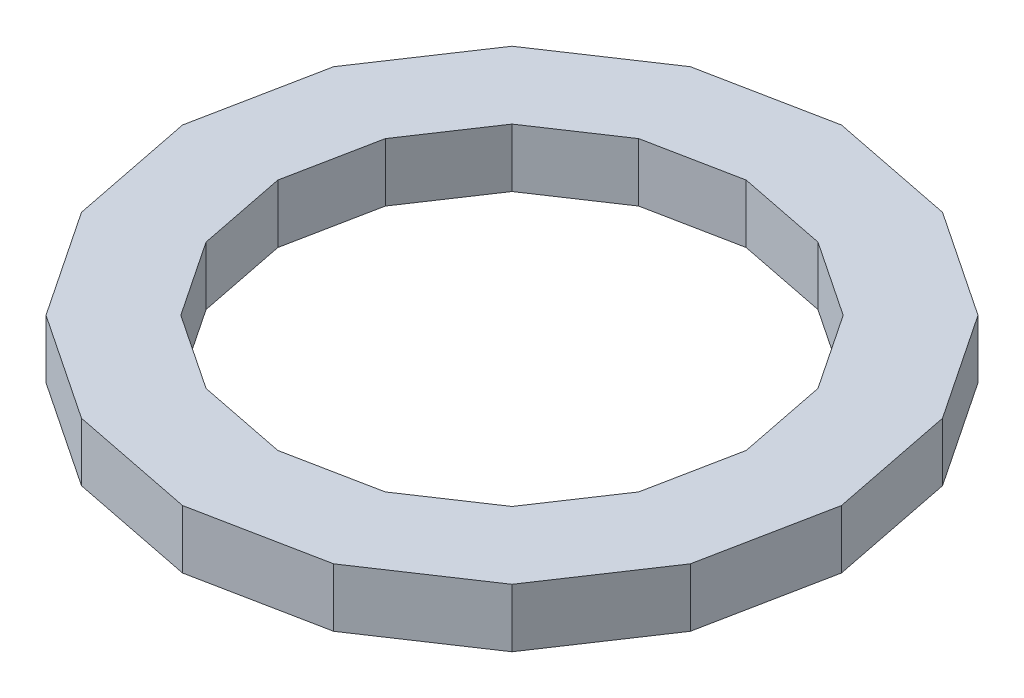
SolidWorks part; units mm, degrees
ref_plane "Front Plane" through (0, 0, 0) normal (0, 0, 1) x (1, 0, 0)
ref_plane "Top Plane" through (0, 0, 0) normal (0, 1, 0) x (1, 0, 0)
ref_plane "Right Plane" through (0, 0, 0) normal (1, 0, 0) x (0, 0, -1)
sketch "Sketch1" plane through (0, 0, 0) normal (0, 1, 0) x (1, 0, 0)
  line L1 (107.4118, 0) -> (99.2356, 41.1047)
  line L2 (99.2356, 41.1047) -> (75.9516, 75.9516)
  line L3 (75.9516, 75.9516) -> (41.1047, 99.2356)
  line L4 (41.1047, 99.2356) -> (0, 107.4118)
  line L5 (0, 107.4118) -> (-41.1047, 99.2356)
  line L6 (-41.1047, 99.2356) -> (-75.9516, 75.9516)
  line L7 (-75.9516, 75.9516) -> (-99.2356, 41.1047)
  line L8 (-99.2356, 41.1047) -> (-107.4118, 0)
  line L9 (-107.4118, 0) -> (-99.2356, -41.1047)
  line L10 (-99.2356, -41.1047) -> (-75.9516, -75.9516)
  line L11 (-75.9516, -75.9516) -> (-41.1047, -99.2356)
  line L12 (-41.1047, -99.2356) -> (0, -107.4118)
  line L13 (0, -107.4118) -> (41.1047, -99.2356)
  line L14 (41.1047, -99.2356) -> (75.9516, -75.9516)
  line L15 (75.9516, -75.9516) -> (99.2356, -41.1047)
  line L16 (99.2356, -41.1047) -> (107.4118, 0)
  line L17 (76.3346, 0) -> (70.524, 29.212)
  line L18 (70.524, 29.212) -> (53.9767, 53.9767)
  line L19 (53.9767, 53.9767) -> (29.212, 70.524)
  line L20 (29.212, 70.524) -> (0, 76.3346)
  line L21 (0, 76.3346) -> (-29.212, 70.524)
  line L22 (-29.212, 70.524) -> (-53.9767, 53.9767)
  line L23 (-53.9767, 53.9767) -> (-70.524, 29.212)
  line L24 (-70.524, 29.212) -> (-76.3346, 0)
  line L25 (-76.3346, 0) -> (-70.524, -29.212)
  line L26 (-70.524, -29.212) -> (-53.9767, -53.9767)
  line L27 (-53.9767, -53.9767) -> (-29.212, -70.524)
  line L28 (-29.212, -70.524) -> (0, -76.3346)
  line L29 (0, -76.3346) -> (29.212, -70.524)
  line L30 (29.212, -70.524) -> (53.9767, -53.9767)
  line L31 (53.9767, -53.9767) -> (70.524, -29.212)
  line L32 (70.524, -29.212) -> (76.3346, 0)
  circle A0 centre (0, 0) radius 105.3479 construction
  circle A1 centre (0, 0) radius 74.8679 construction
  dimension "D1" = 30.48
  dimension "D2" = 41.91
extrude "Boss-Extrude1" add sketch "Sketch1" along normal blind 19.05
